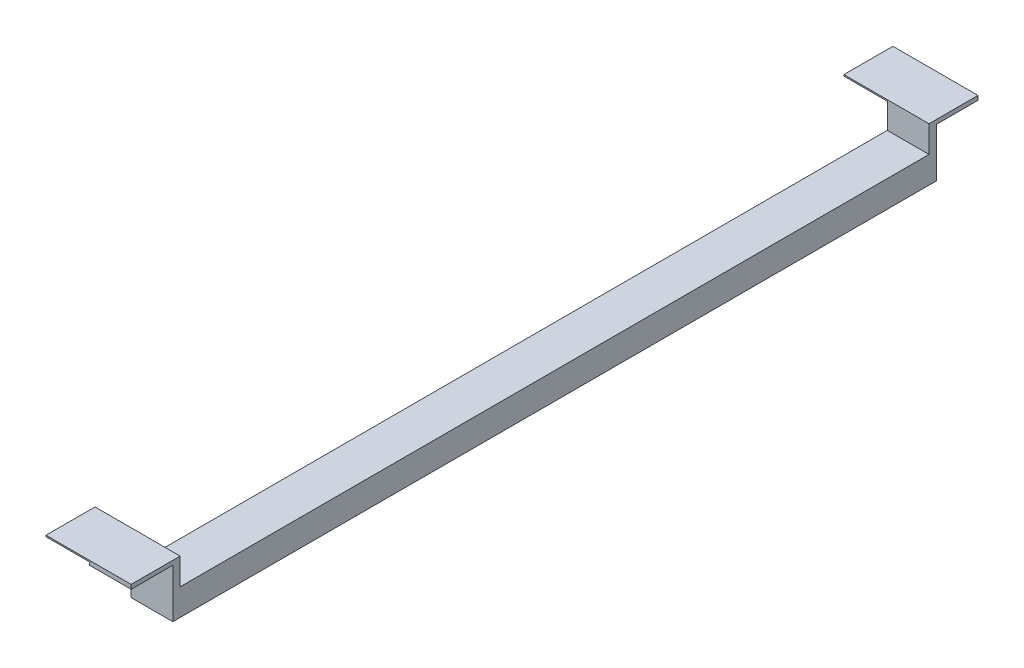
SolidWorks part; units mm, degrees
ref_plane "前视基准面" through (0, 0, 0) normal (0, 0, 1) x (1, 0, 0)
ref_plane "上视基准面" through (0, 0, 0) normal (0, 1, 0) x (1, 0, 0)
ref_plane "右视基准面" through (0, 0, 0) normal (1, 0, 0) x (0, 0, -1)
sketch "草图2" plane through (0, 0, 0) normal (0, 1, 0) x (1, 0, 0)
  line L1 (-14.4929, 79.7445) -> (83.5071, 79.7445)
  line L2 (-14.4929, 79.7445) -> (-14.4929, -18.2555)
  line L3 (-14.4929, -18.2555) -> (83.5071, -18.2555)
  line L4 (83.5071, 79.7445) -> (83.5071, -18.2555)
extrude "凸台-拉伸1" add sketch "草图2" along normal blind 10
sketch "草图3" plane through (0, 0, 18.2555) normal (0, 0, 1) x (1, 0, 0)
  line L1 (-14.4929, 10) -> (83.5071, 10)
  line L2 (-14.4929, 10) -> (-14.4929, -115)
  line L3 (-14.4929, -115) -> (83.5071, -115)
  line L4 (83.5071, 10) -> (83.5071, -115)
extrude "凸台-拉伸2" add sketch "草图3" along normal blind 10
sketch "草图4" plane through (0, 0, 28.2555) normal (0, 0, 1) x (1, 0, 0)
  line L0 (-14.4929, 10) -> (-14.4929, -115) construction
  line L1 (83.5071, -115) -> (-14.4929, -115)
  line L2 (83.5071, -115) -> (83.5071, -52.5)
  line L3 (83.5071, -52.5) -> (-14.4929, -52.5)
  line L4 (-14.4929, -115) -> (-14.4929, -52.5)
extrude "凸台-拉伸3" add sketch "草图4" along normal blind 886.75
mirror "镜向4" about plane through (0, 0, 915.0055) normal (0, 0, 1) of bodies 108
sketch "草图5" plane through (0, 0, 28.2555) normal (0, 0, 1) x (1, 0, 0)
  line L1 (-14.4929, 10) -> (83.5071, 10)
  line L2 (-14.4929, 10) -> (-14.4929, -52.5)
  line L3 (-14.4929, -52.5) -> (83.5071, -52.5)
  line L4 (83.5071, 10) -> (83.5071, -52.5)
extrude "凸台-拉伸4" add sketch "草图5" along normal blind 7.1
sketch "草图6" plane through (0, 0, 1801.7555) normal (0, 0, -1) x (-1, 0, 0)
  line L1 (-83.5071, 10) -> (14.4929, 10)
  line L2 (-83.5071, 10) -> (-83.5071, -52.5)
  line L3 (-83.5071, -52.5) -> (14.4929, -52.5)
  line L4 (14.4929, 10) -> (14.4929, -52.5)
extrude "凸台-拉伸5" add sketch "草图6" along normal blind 7.1
sketch "草图9" plane through (-14.4929, 0, 0) normal (-1, 0, 0) x (0, 0, 1)
  line L0 (35.3555, 10) -> (35.3555, -52.5) construction
  line L1 (-79.7445, 10) -> (35.3555, 10)
  line L2 (-79.7445, 10) -> (-79.7445, 6.8)
  line L3 (-79.7445, 6.8) -> (35.3555, 6.8)
  line L4 (35.3555, 10) -> (35.3555, 6.8)
  line L10 (1909.7555, 10) -> (1909.7555, 0) construction
  line L11 (1794.6555, 10) -> (1909.7555, 10)
  line L12 (1794.6555, 10) -> (1794.6555, 6.8)
  line L13 (1794.6555, 6.8) -> (1909.7555, 6.8)
  line L14 (1909.7555, 10) -> (1909.7555, 6.8)
extrude "凸台-拉伸6" add sketch "草图9" along normal blind 102
